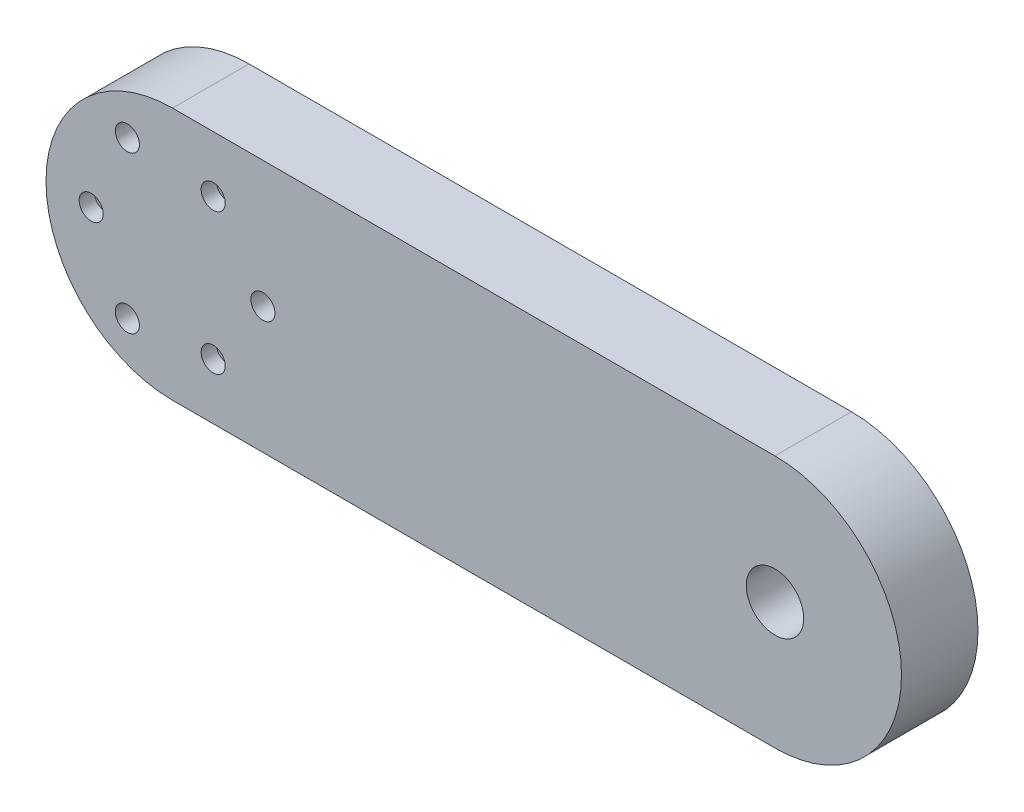
SolidWorks part; units mm, degrees
material "Alloy Steel"
ref_plane "Front Plane" through (0, 0, 0) normal (0, 0, 1) x (1, 0, 0)
ref_plane "Top Plane" through (0, 0, 0) normal (0, 1, 0) x (1, 0, 0)
ref_plane "Right Plane" through (0, 0, 0) normal (1, 0, 0) x (0, 0, -1)
sketch "Sketch1" plane through (0, 0, 0) normal (0, 0, 1) x (1, 0, 0)
  line L0 (0, 0) -> (100, 0) construction
  line L1 (0, 21) -> (100, 21)
  line L2 (0, -21) -> (100, -21)
  arc A1 (0, 21) -> (0, -21) centre (0, 0) ccw
  arc A2 (100, -21) -> (100, 21) centre (100, 0) ccw
  circle A3 centre (100, 0) radius 4.7625
  circle A4 centre (0, 0) radius 15 construction
  circle A5 centre (15, 0) radius 2
  circle A6 centre (-7.5, -12.9904) radius 2
  circle A7 centre (-7.5, 12.9904) radius 2
  point P3 (50, 0)
  point P20 (0, 0)
  dimension "D1" = 9.525
  dimension "D2" = 30
  dimension "D3" = 4
  dimension "D4" = 3
extrude "Boss-Extrude2" add sketch "Sketch1" along normal blind 12.7
sketch "Sketch2" plane through (0, 0, 12.7) normal (0, 0, 1) x (1, 0, 0)
  circle A0 centre (0, 0) radius 13.5 construction
  circle A1 centre (-13.5, 0) radius 2
  circle A2 centre (6.75, 11.6913) radius 2
  circle A3 centre (6.75, -11.6913) radius 2
  point P11 (0, 0)
  dimension "D1" = 27
  dimension "D2" = 4
  dimension "D3" = 3
extrude "Cut-Extrude1" cut sketch "Sketch2" against normal blind 2.5
